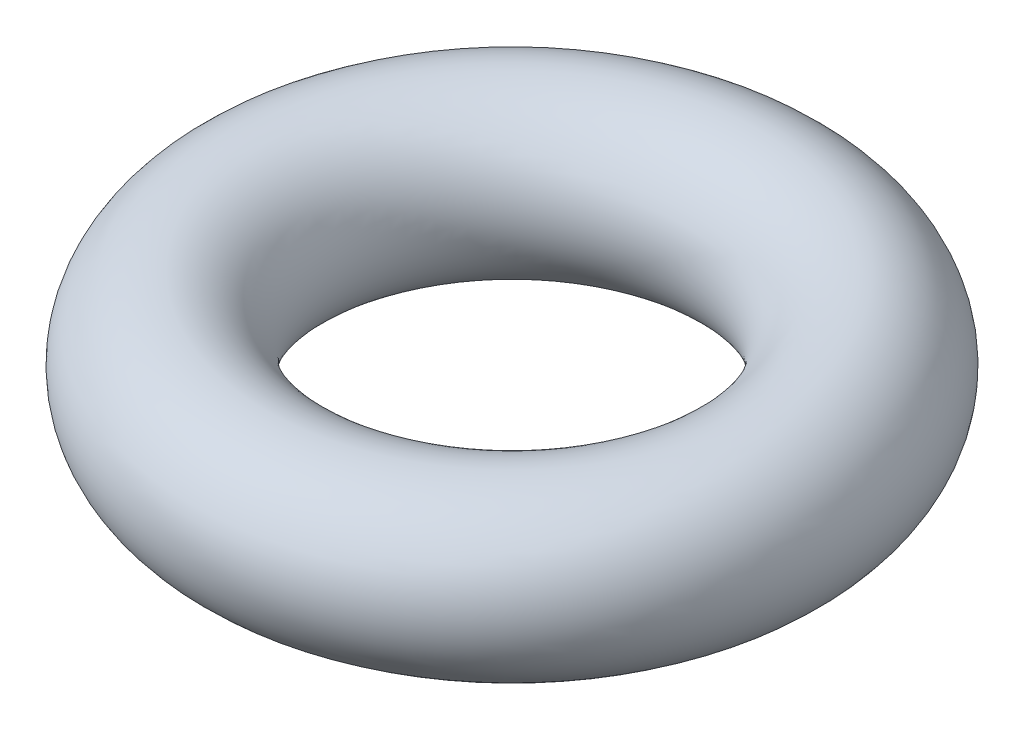
SolidWorks part; units mm, degrees
ref_plane "Front Plane" through (0, 0, 0) normal (0, 0, 1) x (1, 0, 0)
ref_plane "Top Plane" through (0, 0, 0) normal (0, 1, 0) x (1, 0, 0)
ref_plane "Right Plane" through (0, 0, 0) normal (1, 0, 0) x (0, 0, -1)
sketch "Sketch1" plane through (0, 0, 0) normal (0, 0, 1) x (1, 0, 0)
  line L0 (0, -29.9291) -> (0, 1426.0891) construction
  circle A1 centre (2.3876, 0) radius 0.7938
  dimension "D1" = 1.5875
  dimension "D2" = 2.3876
revolve "Revolve1" add sketch "Sketch1" angle 360 about L0
ref_plane "Plane1" through (0, -0.7933, 0) normal (0, 1, 0) x (1, 0, 0)
